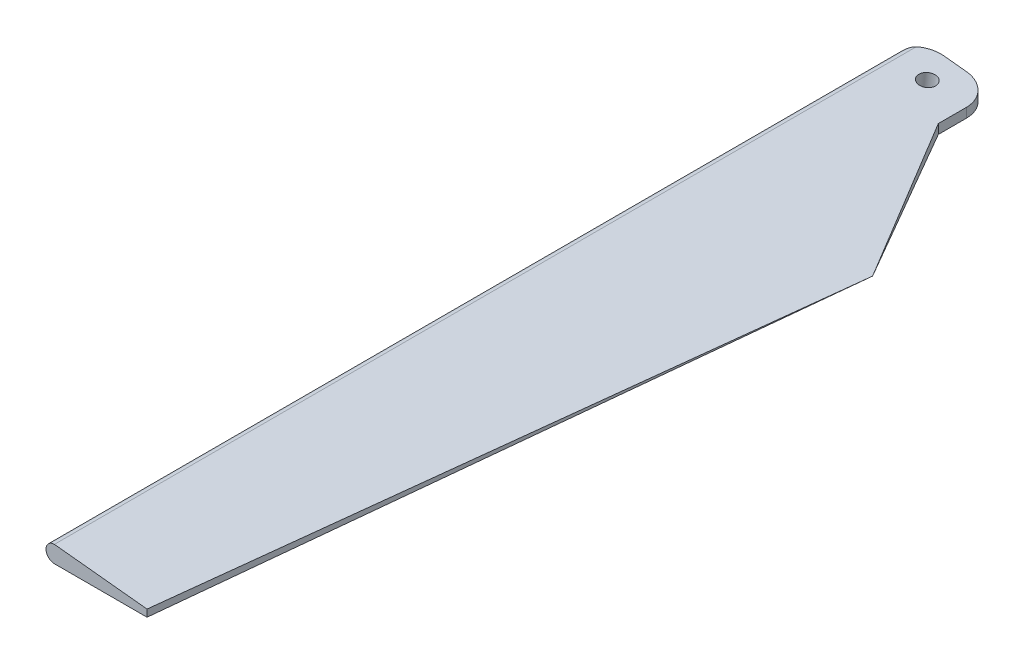
SolidWorks part; units mm, degrees
ref_plane "Alzado" through (0, 0, 0) normal (0, 0, 1) x (1, 0, 0)
ref_plane "Planta" through (0, 0, 0) normal (0, 1, 0) x (1, 0, 0)
ref_plane "Vista lateral" through (0, 0, 0) normal (1, 0, 0) x (0, 0, -1)
sketch "Croquis1" plane through (0, 0, 0) normal (0, 0, 1) x (1, 0, 0)
  line L1 (0, 0) -> (28.5, 0)
  line L6 (28.5, 0) -> (0, 3)
  arc A3 (0, 3) -> (0, 0) centre (0, 1.5) ccw
  dimension "D1" = 1.5
  dimension "D2" = 28.5
extrude "Saliente-Extruir1" add sketch "Croquis1" against normal blind 155
sketch "Croquis2" plane through (0, 0, 0) normal (0, 1, 0) x (1, 0, 0)
  line L0 (-1.5, 0) -> (-1.5, 150)
  line L2 (3.5, 155) -> (7.5, 155)
  line L3 (28.5, 155) -> (0, 155) construction
  line L4 (12.5, 150) -> (12.5, 145)
  line L8 (28.5, 0) -> (0, 0) construction
  line L9 (16.5, 0) -> (-1.5, 0)
  line L10 (12.5, 145) -> (28.5, 117.2872)
  line L12 (28.5, 155) -> (28.5, 0) construction
  line L13 (28.5, 117.2872) -> (-35.4761, 117.2872) construction
  line L14 (28.5, 117.2872) -> (16.5, 0)
  arc A0 (-1.5, 150) -> (3.5, 155) centre (3.5, 150) cw
  arc A1 (12.5, 150) -> (7.5, 155) centre (7.5, 150) ccw
  point P12 (-1.5, 155)
  point P21 (12.5, 155)
  dimension "D5" = 5
  dimension "D1" = 14
  dimension "D2" = 10
  dimension "D3" = 60
  dimension "D4" = 18
sketch "Croquis3" plane through (0, 0, 0) normal (0, 1, 0) x (1, 0, 0)
  line L0 (12.5, 150) -> (12.5, 145) construction
  line L1 (12.5, 145) -> (28.5, 117.2872) construction
  line L2 (28.5, 155) -> (28.5, 0) construction
  line L3 (28.5, 155) -> (0, 155) construction
  line L4 (12.5, 150) -> (12.5, 145)
  line L5 (12.5, 145) -> (28.5, 117.2872)
  line L6 (28.5, 155) -> (28.5, 0)
  line L7 (28.5, 155) -> (7.5, 155)
  line L8 (28.5, 0) -> (0, 0) construction
  line L9 (28.5, 117.2872) -> (16.5, 0) construction
  line L10 (28.5, 0) -> (16.5, 0)
  line L11 (28.5, 117.2872) -> (16.5, 0)
  line L12 (-1.5, 155) -> (3.5, 155)
  line L13 (-1.5, 150) -> (-1.5, 155)
  arc A0 (12.5, 150) -> (7.5, 155) centre (7.5, 150) ccw construction
  arc A1 (12.5, 150) -> (7.5, 155) centre (7.5, 150) ccw
  arc A2 (3.5, 155) -> (-1.5, 150) centre (3.5, 150) ccw
extrude "Cortar-Extruir6" cut sketch "Croquis3" along normal blind 155 contours L6 L11 L10 | A1 L4 L5 L6 L7 | A2 L12 L13
sketch "Croquis5" plane through (0.3123, 2.9671, 0) normal (0.1047, 0.9945, 0) x (0.9945, -0.1047, 0)
  line L0 (12.255, 145) -> (12.255, 150) construction
  line L1 (7.2274, 155) -> (3.2053, 155) construction
  circle A0 centre (5.255, 150) radius 1.5
  dimension "D1" = 7
  dimension "D3" = 3
  dimension "D2" = 5
extrude "Cortar-Extruir9" cut sketch "Croquis5" against normal blind 155
